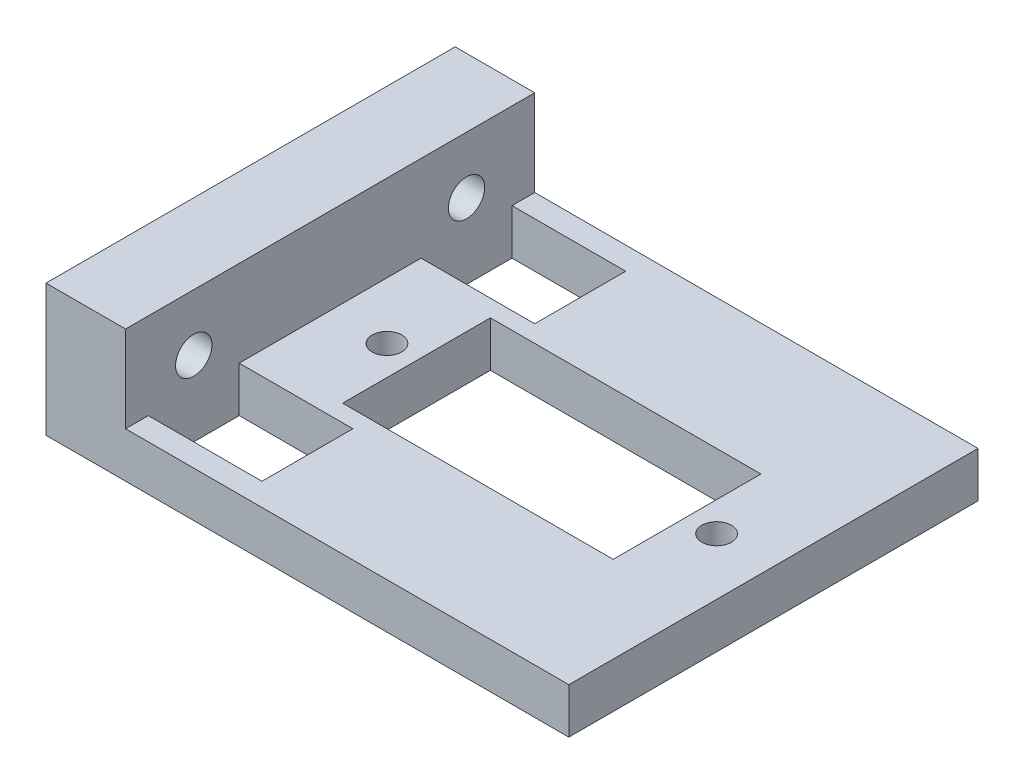
SolidWorks part; units mm, degrees
ref_plane "Front Plane" through (0, 0, 0) normal (0, 0, 1) x (1, 0, 0)
ref_plane "Top Plane" through (0, 0, 0) normal (0, 1, 0) x (1, 0, 0)
ref_plane "Right Plane" through (0, 0, 0) normal (1, 0, 0) x (0, 0, -1)
sketch "Servo_shelf_profile" plane through (0, 0, 0) normal (0, 1, 0) x (1, 0, 0)
  line L1 (-21, -18) -> (25, -18)
  line L2 (-21, -18) -> (-21, 18)
  line L3 (-21, 18) -> (25, 18)
  line L4 (25, -18) -> (25, 18)
  dimension "D1" = 46
  dimension "D2" = 36
extrude "Servo_shelf" add sketch "Servo_shelf_profile" along normal blind 4 from offset 21.4
sketch "Rear_clamping_block_profile" plane through (0, 0, 0) normal (0, 0, 1) x (1, 0, 0)
  line L1 (-21, 23) -> (-14, 23)
  line L2 (-21, 23) -> (-21, 33)
  line L3 (-21, 33) -> (-14, 33)
  line L4 (-14, 23) -> (-14, 33)
  dimension "D1" = 7
  dimension "D2" = 10
extrude "Rear_clamping_block" add sketch "Rear_clamping_block_profile" along normal blind 36 from offset 18
sketch "Servo_body_window_profile" plane through (0, 0, 0) normal (0, 1, 0) x (1, 0, 0)
  line L1 (-6.4, -6.5) -> (17.4, -6.5)
  line L2 (-6.4, -6.5) -> (-6.4, 6.5)
  line L3 (-6.4, 6.5) -> (17.4, 6.5)
  line L4 (17.4, -6.5) -> (17.4, 6.5)
  dimension "D1" = 23.8
  dimension "D2" = 13
extrude "Servo_body_window" cut sketch "Servo_body_window_profile" along normal through all from offset 20.4
sketch "Yaw_servo_M2_fasteners_profile" plane through (0, 0, 0) normal (0, 1, 0) x (1, 0, 0)
  circle A0 centre (-9, 0) radius 1.3
  circle A1 centre (20, 0) radius 1.3
  dimension "D1" = 2.6
  dimension "D2" = 2.6
extrude "Yaw_servo_M2_fasteners" cut sketch "Yaw_servo_M2_fasteners_profile" along normal through all from offset 20.4
sketch "Left_nut_access_profile" plane through (0, 0, 0) normal (0, 1, 0) x (1, 0, 0)
  line L1 (-14, 8) -> (-4, 8)
  line L2 (-14, 8) -> (-14, 16)
  line L3 (-14, 16) -> (-4, 16)
  line L4 (-4, 8) -> (-4, 16)
  dimension "D1" = 10
  dimension "D2" = 8
extrude "Left_nut_access" cut sketch "Left_nut_access_profile" along normal through all from offset 20
sketch "Right_nut_access_profile" plane through (0, 0, 0) normal (0, 1, 0) x (1, 0, 0)
  line L1 (-14, -16) -> (-4, -16)
  line L2 (-14, -16) -> (-14, -8)
  line L3 (-14, -8) -> (-4, -8)
  line L4 (-4, -16) -> (-4, -8)
  dimension "D1" = 10
  dimension "D2" = 8
extrude "Right_nut_access" cut sketch "Right_nut_access_profile" along normal through all from offset 20
sketch "Rear_clamping_M3_profile" plane through (0, 0, 0) normal (1, 0, 0) x (0, 0, -1)
  circle A0 centre (12, 28) radius 1.6
  circle A1 centre (-12, 28) radius 1.6
  dimension "D1" = 3.2
  dimension "D2" = 3.2
extrude "Rear_clamping_M3_holes" cut sketch "Rear_clamping_M3_profile" along normal blind 11 from offset 25
